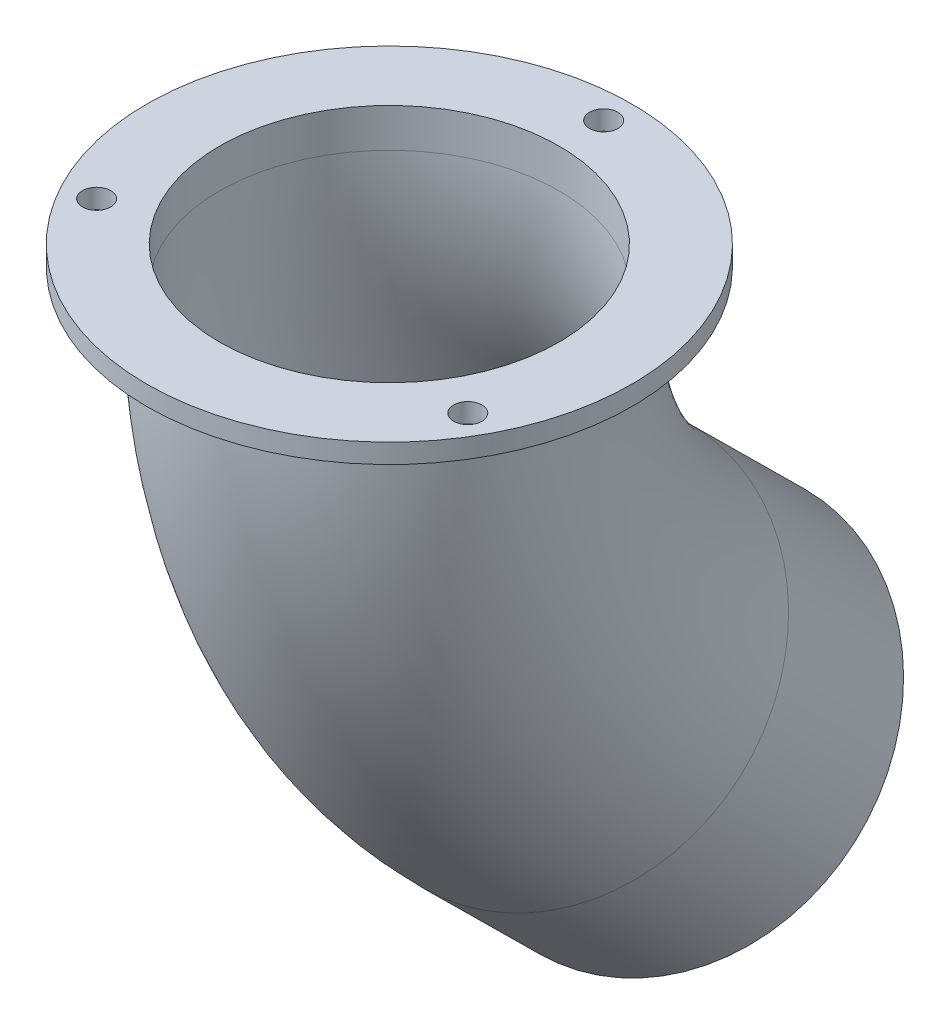
SolidWorks part; units mm, degrees
ref_plane "Front Plane" through (0, 0, 0) normal (0, 0, 1) x (1, 0, 0)
ref_plane "Top Plane" through (0, 0, 0) normal (0, 1, 0) x (1, 0, 0)
ref_plane "Right Plane" through (0, 0, 0) normal (1, 0, 0) x (0, 0, -1)
sketch "Sketch1" plane through (0, 0, 0) normal (1, 0, 0) x (0, 0, -1)
  line L0 (0, 0) -> (0, -70) construction
  line L1 (0, -70) -> (70, -70) construction
  line L3 (0, 0) -> (0, -2.4)
  line L4 (0, -2.4) -> (70, -2.4) construction
  line L5 (35.6055, -36.7838) -> (16.0656, -57.018) construction
  line L6 (35.6055, -36.7838) -> (0, -2.4) construction
  line L7 (20.7616, -52.1552) -> (34.9773, -66.2233)
  arc A0 (0, -2.4) -> (20.7616, -52.1552) centre (70, -2.4) ccw
  dimension "D1" = 46
  dimension "D5" = 70
  dimension "D6" = 20
  dimension "D2" = 70
  dimension "D3" = 70
  dimension "D4" = 2.4
sketch "Sketch2" plane through (0, 0, 0) normal (0, 1, 0) x (1, 0, 0)
  circle A0 centre (0, 0) radius 21
  circle A1 centre (0, 0) radius 23.4
  dimension "D1" = 2.4
  dimension "D2" = 42
sweep "Sweep1" add profiles "Sketch2" path "Sketch1"
sketch "Sketch4" plane through (0, 0, 0) normal (0, 1, 0) x (1, 0, 0)
  line L0 (0, 0) -> (0, 26.5) construction
  circle A0 centre (0, 0) radius 21
  circle A1 centre (0, 0) radius 30
  circle A2 centre (0, 26.5) radius 1.75
  circle A3 centre (22.9497, -13.25) radius 1.75
  circle A4 centre (-22.9497, -13.25) radius 1.75
  point P14 (0, 0)
  dimension "D1" = 26.5
  dimension "D2" = 60
  dimension "D3" = 3.5
  dimension "D4" = 3
extrude "Boss-Extrude1" add sketch "Sketch4" along normal blind 2.4
